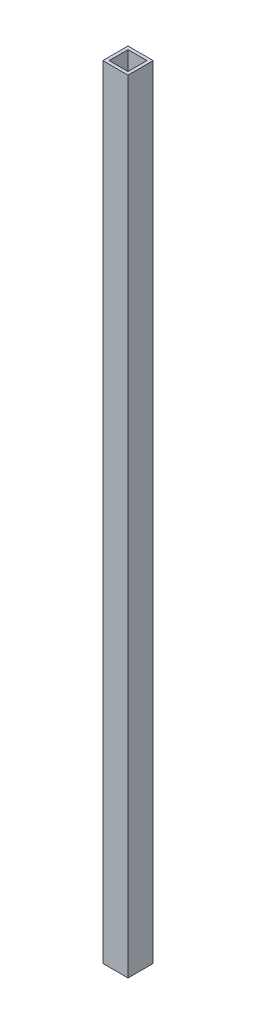
SolidWorks part; units mm, degrees
material "1060 Alloy"
ref_plane "Front Plane" through (0, 0, 0) normal (0, 0, 1) x (1, 0, 0)
ref_plane "Top Plane" through (0, 0, 0) normal (0, 1, 0) x (1, 0, 0)
ref_plane "Right Plane" through (0, 0, 0) normal (1, 0, 0) x (0, 0, -1)
sketch "Sketch2" plane through (0, 0, 0) normal (0, 1, 0) x (1, 0, 0)
  line L1 (0, 0) -> (25.4, 0)
  line L2 (0, 0) -> (0, 25.4)
  line L3 (0, 25.4) -> (25.4, 25.4)
  line L4 (25.4, 0) -> (25.4, 25.4)
  line L5 (3.175, 3.175) -> (22.225, 3.175)
  line L6 (3.175, 3.175) -> (3.175, 22.225)
  line L7 (3.175, 22.225) -> (22.225, 22.225)
  line L8 (22.225, 3.175) -> (22.225, 22.225)
  dimension "D1" = 25.4
  dimension "D2" = 25.4
  dimension "D3" = 3.175
  dimension "D4" = 3.175
  dimension "D5" = 3.175
  dimension "D6" = 3.175
extrude "Boss-Extrude1" add sketch "Sketch2" along normal blind 787.4
sketch "Sketch3" plane through (0, 0, -25.4) normal (0, 0, -1) x (-1, 0, 0)
  line L0 (0, 787.4) -> (0, 0) construction
  circle A0 centre (-14.2875, 393.7) radius 6.35
  circle A1 centre (-11.1125, 647.7) radius 6.35
  circle A2 centre (-11.1125, 139.7) radius 6.35
  dimension "D1" = 12.7
  dimension "D3" = 12.7
  dimension "D6" = 12.7
  dimension "D2" = 14.2875
  dimension "D4" = 11.1125
  dimension "D5" = 254
  dimension "D7" = 11.1125
  dimension "D8" = 254
